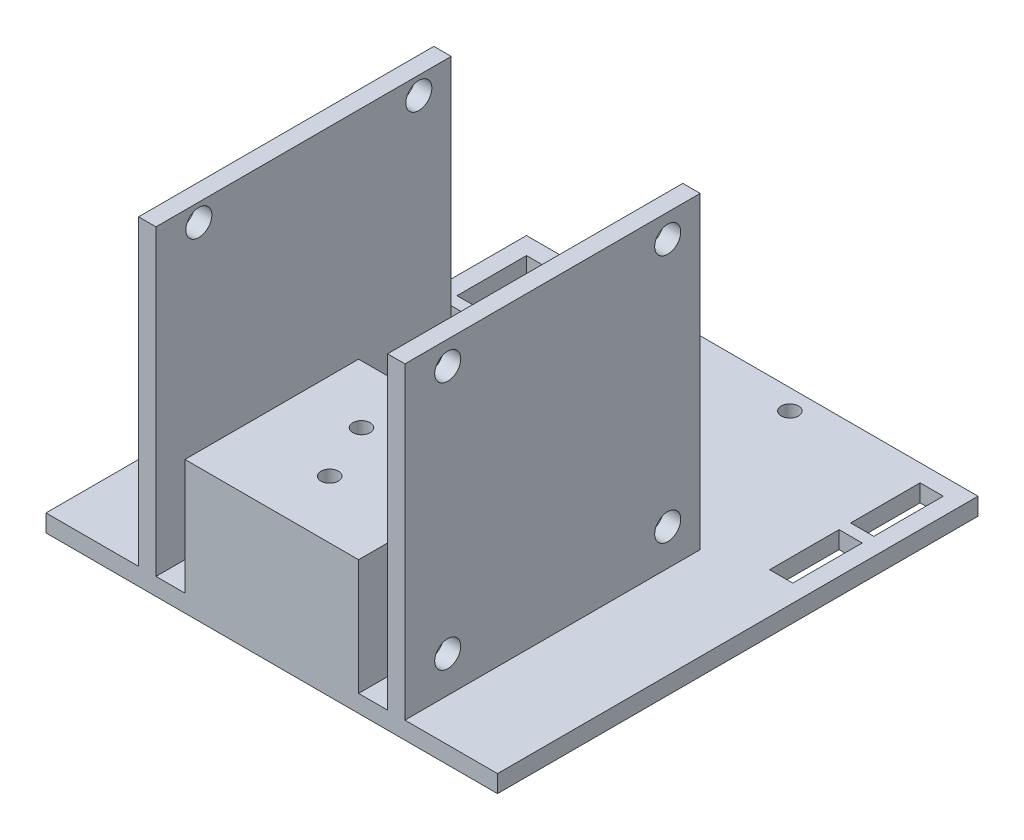
SolidWorks part; units mm, degrees
ref_plane "Front Plane" through (0, 0, 0) normal (0, 0, 1) x (1, 0, 0)
ref_plane "Top Plane" through (0, 0, 0) normal (0, 1, 0) x (1, 0, 0)
ref_plane "Right Plane" through (0, 0, 0) normal (1, 0, 0) x (0, 0, -1)
sketch "Sketch1" plane through (0, 0, 0) normal (0, 1, 0) x (1, 0, 0)
  line L1 (0, 0) -> (148, 0)
  line L2 (0, 0) -> (0, 115)
  line L3 (0, 115) -> (148, 115)
  line L4 (148, 0) -> (148, 115)
  line L5 (59, 30) -> (89, 30)
  line L6 (59, 30) -> (59, 0)
  line L7 (59, 0) -> (89, 0)
  line L8 (89, 30) -> (89, 0)
  circle A0 centre (143, 110) radius 2.25
  circle A1 centre (128, 110) radius 2.25
  circle A2 centre (113, 110) radius 2.25
  circle A3 centre (143, 56) radius 2.25
  circle A4 centre (128, 56) radius 2.25
  circle A5 centre (113, 56) radius 2.25
  circle A7 centre (5, 110) radius 2.25
  circle A8 centre (5, 56) radius 2.25
  circle A9 centre (20, 110) radius 2.25
  circle A10 centre (35, 110) radius 2.25
  circle A11 centre (20, 56) radius 2.25
  circle A12 centre (35, 56) radius 2.25
  circle A13 centre (74, 10) radius 1.5
  circle A14 centre (69.5, 20) radius 1.5
  circle A15 centre (78.5, 20) radius 1.5
  dimension "D3" = 4.5
  dimension "D4" = 30
  dimension "D9" = 15
  dimension "D10" = 15
  dimension "D11" = 15
  dimension "D12" = 54
  dimension "D13" = 15
  dimension "D14" = 15
  dimension "D1" = 148
  dimension "D2" = 115
  dimension "D5" = 30
  dimension "D6" = 59
  dimension "D7" = 59
  dimension "D8" = 15
  dimension "D15" = 54
extrude "Boss-Extrude4" add sketch "Sketch1" along normal blind 3 contours L2 L1 L4 L3
sketch "Sketch2" plane through (0, 3, 0) normal (0, 1, 0) x (1, 0, 0)
  circle A0 centre (5, 110) radius 2.25
extrude "Cut-Extrude1" cut sketch "Sketch2" against normal blind 3
sketch "Sketch3" plane through (0, 3, 0) normal (0, 1, 0) x (1, 0, 0)
  circle A0 centre (143, 110) radius 2.25
extrude "Cut-Extrude2" cut sketch "Sketch3" against normal blind 3
sketch "Sketch4" plane through (0, 3, 0) normal (0, 1, 0) x (1, 0, 0)
  circle A0 centre (5, 56) radius 2.25
extrude "Cut-Extrude3" cut sketch "Sketch4" against normal blind 3
sketch "Sketch5" plane through (0, 3, 0) normal (0, 1, 0) x (1, 0, 0)
  line L0 (0, 0) -> (148, 0) construction
  line L1 (59, 30) -> (89, 30)
  line L2 (59, 30) -> (59, 0)
  line L3 (59, 0) -> (89, 0)
  line L4 (89, 30) -> (89, 0)
  line L5 (0, 0) -> (0, 115) construction
  line L6 (148, 0) -> (148, 115) construction
  line L7 (0, 115) -> (148, 115) construction
  dimension "D1" = 59
  dimension "D2" = 59
  dimension "D3" = 30
  dimension "D4" = 30
  dimension "D5" = 85
extrude "Boss-Extrude7" add sketch "Sketch5" along normal blind 20
sketch "Sketch6" plane through (0, 3, 0) normal (0, 1, 0) x (1, 0, 0)
  circle A0 centre (20, 110) radius 2.25
  circle A1 centre (35, 110) radius 2.25
  circle A2 centre (20, 56) radius 2.25
  circle A3 centre (35, 56) radius 2.25
  circle A4 centre (128, 110) radius 2.25
  circle A5 centre (113, 110) radius 2.25
  circle A6 centre (113, 56) radius 2.25
  circle A7 centre (128, 56) radius 2.25
  circle A8 centre (143, 56) radius 2.25
extrude "Cut-Extrude4" cut sketch "Sketch6" against normal blind 10
sketch "Sketch7" plane through (0, 23, 0) normal (0, 1, 0) x (1, 0, 0)
  circle A0 centre (69.5, 20) radius 1.5
  circle A1 centre (74, 10) radius 1.5
  circle A2 centre (78.5, 20) radius 1.5
extrude "Cut-Extrude5" cut sketch "Sketch7" against normal blind 30
sketch "Sketch8" plane through (0, 3, 0) normal (0, 1, 0) x (1, 0, 0)
  line L0 (89, 0) -> (148, 0) construction
  line L1 (94, 51) -> (97, 51)
  line L2 (94, 51) -> (94, 0)
  line L3 (94, 0) -> (97, 0)
  line L4 (97, 51) -> (97, 0)
  dimension "D1" = 51
sketch "Sketch9" plane through (0, 0, 0) normal (0, -1, 0) x (-1, 0, 0)
  line L6 (-51, 0) -> (-54, 0)
  line L7 (-51, 0) -> (-51, 51)
  line L8 (-51, 51) -> (-54, 51)
  line L9 (-54, 0) -> (-54, 51)
sketch "Sketch10" plane through (0, 3, 0) normal (0, 1, 0) x (1, 0, 0)
  line L1 (128, 51.38) -> (148, 51.38)
  line L2 (128, 51.38) -> (128, 0)
  line L3 (128, 0) -> (148, 0)
  line L4 (148, 51.38) -> (148, 0)
extrude "Cut-Extrude6" cut sketch "Sketch10" against normal blind 51.3
sketch "Sketch11" plane through (0, 3, 0) normal (0, 1, 0) x (1, 0, 0)
  line L1 (-0.3537, 0) -> (20, 0)
  line L2 (-0.3537, 0) -> (-0.3537, 51.38)
  line L3 (-0.3537, 51.38) -> (20, 51.38)
  line L4 (20, 0) -> (20, 51.38)
extrude "Cut-Extrude7" cut sketch "Sketch11" against normal blind 51.3
sketch "Sketch13" plane through (0, 3, 0) normal (0, 1, 0) x (1, 0, 0)
  line L0 (20, 0) -> (20, 51.38) construction
  line L1 (25, 46) -> (30, 46)
  line L2 (25, 46) -> (25, 32)
  line L3 (25, 32) -> (30, 32)
  line L4 (30, 46) -> (30, 32)
  line L5 (25, 30) -> (30, 30)
  line L6 (25, 30) -> (25, 16)
  line L7 (25, 16) -> (30, 16)
  line L8 (30, 30) -> (30, 16)
  line L9 (118, 46) -> (123, 46)
  line L10 (118, 46) -> (118, 32)
  line L11 (118, 32) -> (123, 32)
  line L12 (123, 46) -> (123, 32)
  line L13 (128, 51.38) -> (128, 0) construction
  line L15 (118, 30) -> (123, 30)
  line L16 (118, 30) -> (118, 16)
  line L17 (118, 16) -> (123, 16)
  line L18 (123, 30) -> (123, 16)
  dimension "D1" = 5
  dimension "D2" = 5
  dimension "D3" = 14
extrude "Cut-Extrude8" cut sketch "Sketch13" against normal blind 51.3
extrude "Boss-Extrude11" add sketch "Sketch8" along normal blind 53.3
extrude "Boss-Extrude12" add sketch "Sketch9" against normal blind 55.3
sketch "Sketch14" plane through (97, 0, 0) normal (1, 0, 0) x (0, 0, -1)
  circle A0 centre (45.4, 52.25) radius 2.25
  circle A1 centre (7.4, 9.25) radius 2.25
sketch "Sketch15" plane through (97, 0, 0) normal (1, 0, 0) x (0, 0, -1)
  circle A0 centre (45.4, 9.25) radius 2.25
  circle A1 centre (7.15, 52.25) radius 2.25
extrude "Cut-Extrude12" cut sketch "Sketch15" against normal blind 53.3 contours A0
extrude "Cut-Extrude13" cut sketch "Sketch14" against normal blind 53.3
sketch "Sketch17" plane through (97, 0, 0) normal (1, 0, 0) x (0, 0, -1)
  circle A0 centre (7.4, 52.25) radius 2.25
extrude "Cut-Extrude14" cut sketch "Sketch17" against normal blind 53.3 contours A0
sketch "Sketch18" plane through (0, 3, 0) normal (0, 1, 0) x (1, 0, 0)
  line L1 (128, 0) -> (113, 0)
  line L2 (128, 0) -> (128, 51.38)
  line L3 (128, 51.38) -> (113, 51.38)
  line L4 (113, 0) -> (113, 51.38)
  line L5 (20, 0) -> (35, 0)
  line L6 (20, 0) -> (20, 51.38)
  line L7 (20, 51.38) -> (35, 51.38)
  line L8 (35, 0) -> (35, 51.38)
  point P9 (0, 0)
  point P11 (0, 0)
  point P12 (0, 0)
  point P13 (0, 0)
  point P14 (0, 0)
  point P15 (0, 0)
  point P17 (0, 0)
  point P18 (0, 0)
extrude "Cut-Extrude15" cut sketch "Sketch18" against normal blind 10
sketch "Sketch19" plane through (0, 3, 0) normal (0, 1, 0) x (1, 0, 0)
  line L1 (1.7132, 113.5553) -> (146.715, 113.5553)
  line L2 (1.7132, 113.5553) -> (1.7132, 52.4586)
  line L3 (1.7132, 52.4586) -> (146.715, 52.4586)
  line L4 (146.715, 113.5553) -> (146.715, 52.4586)
extrude "Boss-Extrude13" add sketch "Sketch19" against normal blind 3
sketch "Sketch20" plane through (0, 3, 0) normal (0, 1, 0) x (1, 0, 0)
  circle A0 centre (64, 79.5) radius 1.5
  circle A1 centre (84, 79.5) radius 1.5
  circle A2 centre (64, 54.5) radius 1.5
  circle A3 centre (84, 54.5) radius 1.5
extrude "Cut-Extrude16" cut sketch "Sketch20" against normal blind 43
sketch "Sketch21" plane through (0, 0, 0) normal (0, -1, 0) x (-1, 0, 0)
  line L1 (-154.4416, 118) -> (-113, 118)
  line L2 (-154.4416, 118) -> (-154.4416, 51.38)
  line L3 (-154.4416, 51.38) -> (-113, 51.38)
  line L4 (-113, 118) -> (-113, 51.38)
  line L5 (-35, 123.5909) -> (6.1202, 123.5909)
  line L6 (-35, 123.5909) -> (-35, 51.38)
  line L7 (-35, 51.38) -> (6.1202, 51.38)
  line L8 (6.1202, 123.5909) -> (6.1202, 51.38)
  line L9 (-25, 83) -> (-134.7482, 83)
  line L10 (-25, 83) -> (-25, 134.9757)
  line L11 (-25, 134.9757) -> (-134.7482, 134.9757)
  line L12 (-134.7482, 83) -> (-134.7482, 134.9757)
  point P12 (0, 0)
  point P14 (-154.4416, 46.3882)
  point P16 (0, 0)
  point P17 (0, 0)
  point P19 (2.172, 48.9089)
  point P20 (6.1202, 123.5909)
  point P22 (0, 0)
  point P23 (-134.7482, 136.6336)
  point P24 (-29.6544, 134.9757)
  point P25 (-25.0816, 83.9062)
extrude "Cut-Extrude18" cut sketch "Sketch21" against normal blind 43 contours L10 L9 L12 L11
ref_plane "Plane1" through (134.7482, 0, -83) normal (1, 0, 0) x (0, 0, -1)
sketch "Sketch23" plane through (0, 0, 0) normal (0, -1, 0) x (1, 0, 0)
  line L1 (152.731, -120.0169) -> (113, -120.0169)
  line L2 (152.731, -120.0169) -> (152.731, -51.38)
  line L3 (152.731, -51.38) -> (113, -51.38)
  line L4 (113, -120.0169) -> (113, -51.38)
  point P4 (152.731, -120.0169)
  point P6 (0, 0)
  point P8 (0, 0)
extrude "Cut-Extrude19" cut sketch "Sketch23" against normal blind 43
sketch "Sketch24" plane through (0, 0, 0) normal (0, -1, 0) x (-1, 0, 0)
  line L1 (-35, 51.38) -> (2.9311, 51.38)
  line L2 (-35, 51.38) -> (-35, 116.8998)
  line L3 (-35, 116.8998) -> (2.9311, 116.8998)
  line L4 (2.9311, 51.38) -> (2.9311, 116.8998)
  point P4 (2.9311, 116.8998)
  point P6 (0, 0)
extrude "Cut-Extrude20" cut sketch "Sketch24" against normal blind 43
sketch "Sketch25" plane through (0, 0, 0) normal (0, -1, 0) x (1, 0, 0)
  line L1 (42, -80) -> (38, -80)
  line L2 (42, -80) -> (42, -68)
  line L3 (42, -68) -> (38, -68)
  line L4 (38, -80) -> (38, -68)
  line L5 (42, -66) -> (38, -66)
  line L6 (42, -66) -> (42, -54)
  line L7 (42, -54) -> (38, -54)
  line L8 (38, -66) -> (38, -54)
  line L9 (110, -80) -> (106, -80)
  line L10 (110, -80) -> (110, -68)
  line L11 (110, -68) -> (106, -68)
  line L12 (106, -80) -> (106, -68)
  line L13 (110, -66) -> (106, -66)
  line L14 (110, -66) -> (110, -54)
  line L15 (110, -54) -> (106, -54)
  line L16 (106, -66) -> (106, -54)
  point P16 (0, 0)
  point P17 (0, 0)
  point P19 (0, 0)
  point P20 (0, 0)
  point P21 (0, 0)
  point P22 (0, 0)
  point P23 (0, 0)
  point P24 (0, 0)
  point P25 (0, 0)
  point P26 (0, 0)
  point P27 (0, 0)
  point P28 (0, 0)
  point P29 (0, 0)
  point P30 (0, 0)
  point P31 (0, 0)
  point P32 (0, 0)
  point P34 (0, 0)
  point P35 (0, 0)
  point P36 (0, 0)
  point P37 (0, 0)
  point P38 (0, 0)
  point P39 (0, 0)
  point P40 (0, 0)
  point P41 (0, 0)
  point P42 (0, 0)
  point P43 (0, 0)
  point P44 (0, 0)
  point P45 (0, 0)
  point P46 (0, 0)
  point P47 (0, 0)
  point P48 (0, 0)
  point P49 (0, 0)
  point P50 (0, 0)
  point P51 (0, 0)
  point P52 (0, 0)
  point P53 (0, 0)
  point P54 (0, 0)
extrude "Cut-Extrude23" cut sketch "Sketch25" against normal blind 43 contours L2 L1 L4 L3 | L6 L5 L8 L7 | L10 L9 L12 L11 | L14 L13 L16 L15
